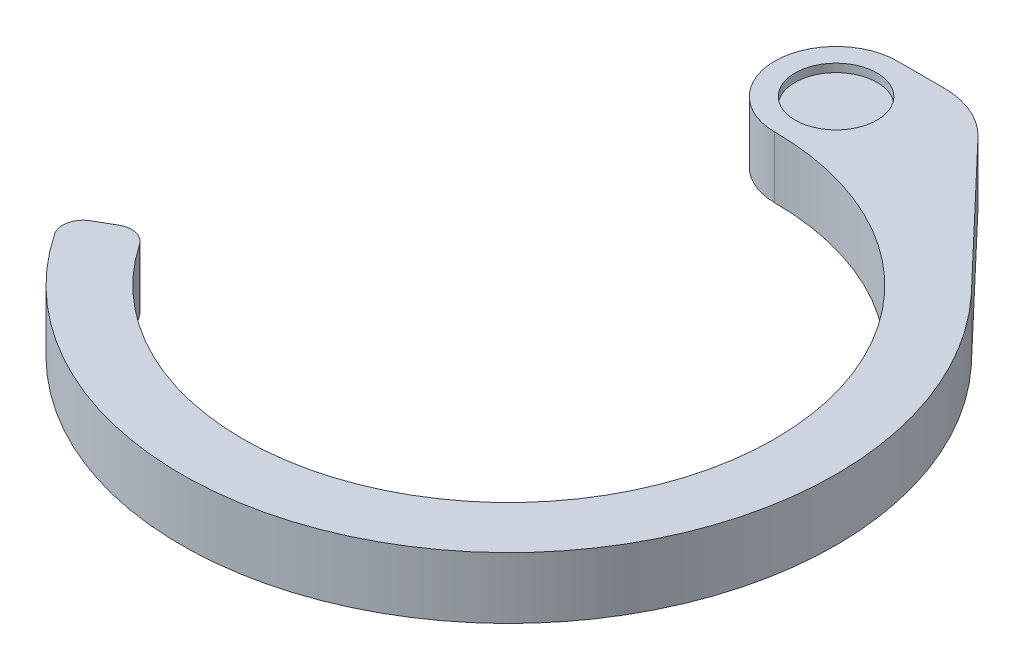
SolidWorks part; units mm, degrees
ref_plane "正面" through (0, 0, 0) normal (0, 0, 1) x (1, 0, 0)
ref_plane "平面" through (0, 0, 0) normal (0, 1, 0) x (1, 0, 0)
ref_plane "右側面" through (0, 0, 0) normal (1, 0, 0) x (0, 0, -1)
sketch "ｽｹｯﾁ2" plane through (0, 0, 0) normal (0, 1, 0) x (1, 0, 0)
  line L1 (-1.8089, 2.6033) -> (0, 0)
  line L2 (-60.4669, -34.9106) -> (-64.8074, -37.4166)
  line L4 (0, 95) -> (11.4274, 95)
  line L5 (25.9115, 88.7917) -> (58.5757, 54.4875)
  arc A0 (-66.4612, -44.5298) -> (57.2894, 55.8384) centre (0, 0) ccw
  arc A1 (-53.8264, -36.4378) -> (0, 65) centre (0, 0) ccw
  arc A2 (0, 95) -> (0, 65) centre (0, 80) ccw
  arc A3 (11.4274, 95) -> (25.9115, 88.7917) centre (11.4274, 75) cw
  arc A4 (-53.8264, -36.4378) -> (-60.4669, -34.9106) centre (-57.9669, -39.2407) ccw
  arc A5 (-66.4612, -44.5298) -> (-64.8074, -37.4166) centre (-62.3074, -41.7467) cw
  dimension "D1" = 160
  dimension "D2" = 130
  dimension "D4" = 20
  dimension "D5" = 5
  dimension "D6" = 5
extrude "ﾎﾞｽ - 押し出し4" add sketch "ｽｹｯﾁ2" along normal blind 15 contours A5 A0 L5 A3 L4 A2 A1 A4 L2
sketch "ｽｹｯﾁ3" plane through (0, 15, 0) normal (0, 1, 0) x (1, 0, 0)
  circle A0 centre (0, 80) radius 10
  dimension "D1" = 20
extrude "ｶｯﾄ - 押し出し1" cut sketch "ｽｹｯﾁ3" against normal blind 2
